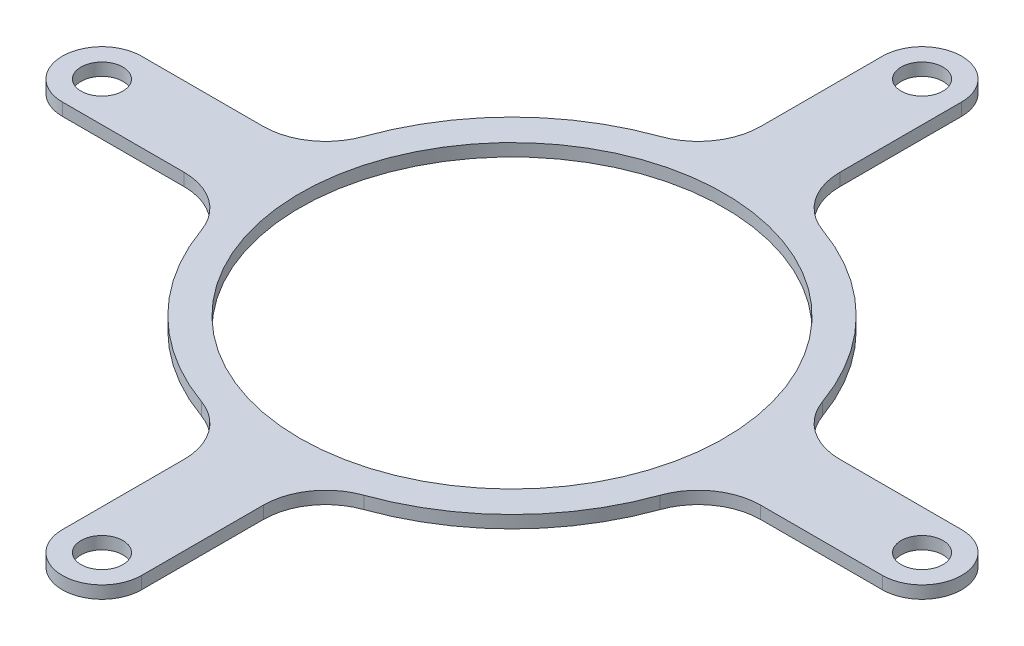
SolidWorks part; units mm, degrees
ref_plane "Front Plane" through (0, 0, 0) normal (0, 0, 1) x (1, 0, 0)
ref_plane "Top Plane" through (0, 0, 0) normal (0, 1, 0) x (1, 0, 0)
ref_plane "Right Plane" through (0, 0, 0) normal (1, 0, 0) x (0, 0, -1)
sketch "Sketch1" plane through (0, 0, 0) normal (0, 1, 0) x (1, 0, 0)
  circle A0 centre (0, 0) radius 34
  circle A1 centre (0, 0) radius 39
  dimension "innerDiam" = 68
  dimension "outerDiam" = 78
extrude "Boss-Extrude1" add sketch "Sketch1" along normal mid plane 2
sketch "Sketch2" plane through (0, 1, 0) normal (0, 1, 0) x (1, 0, 0)
  line L0 (0, 0) -> (0, 38.8704) construction
  line L1 (-6.35, 46.1917) -> (-6.35, 65.7)
  line L2 (6.35, 65.7) -> (6.35, 46.1917)
  arc A0 (-6.35, 65.7) -> (6.35, 65.7) centre (0, 65.7) cw
  arc A1 (6.35, 46.1917) -> (13.0133, 36.7649) centre (16.35, 46.1917) ccw
  circle A2 centre (0, 0) radius 39 construction
  arc A3 (-6.35, 46.1917) -> (-13.0133, 36.7649) centre (-16.35, 46.1917) cw
  arc A4 (13.0133, 36.7649) -> (-13.0133, 36.7649) centre (0, 0) ccw
  circle A5 centre (0, 0) radius 65.7 construction
  circle A6 centre (0, 65.7) radius 3.35
  dimension "supportsDiam" = 131.4
  dimension "rodDiam" = 6.7
  dimension "D3" = 3
  dimension "D4" = 10
extrude "Boss-Extrude2" add sketch "Sketch2" against normal up to surface (2 mm away) up to face at (0, -1, 39)
pattern_circular "CirPattern1" count 4 over 360 about axis through (0, 0, 0) along (0, 1, 0) of "Boss-Extrude2"
